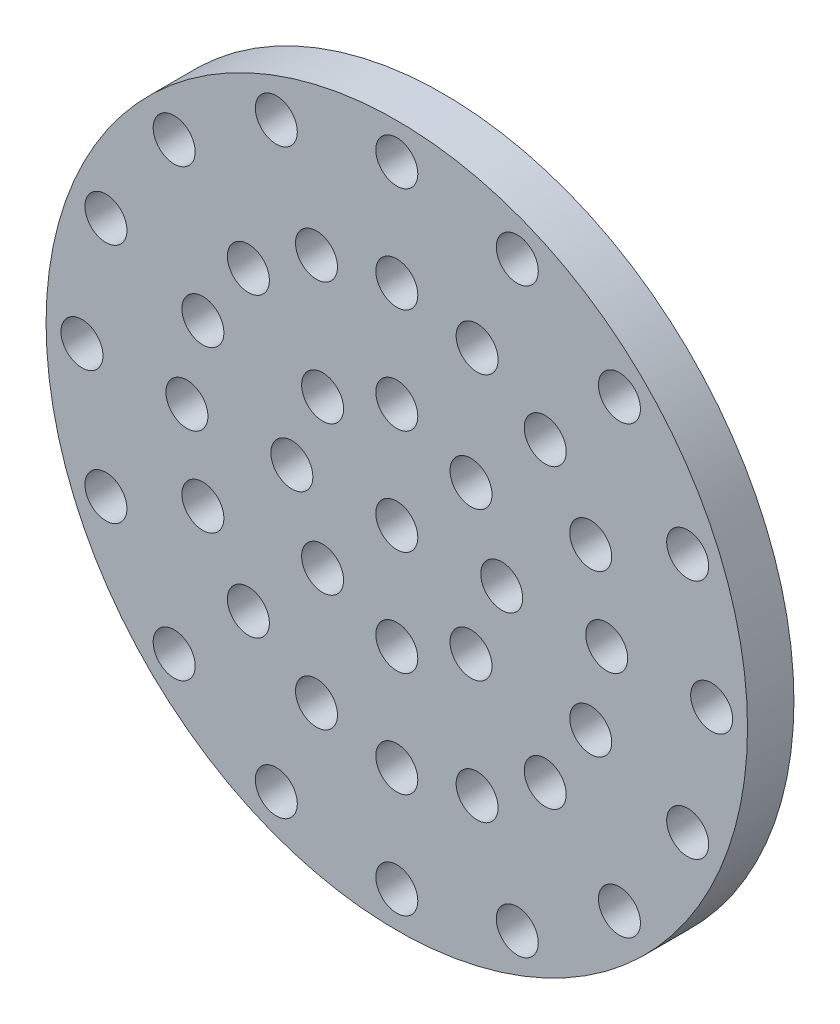
SolidWorks part; units mm, degrees
ref_plane "Front Plane" through (0, 0, 0) normal (0, 0, 1) x (1, 0, 0)
ref_plane "Top Plane" through (0, 0, 0) normal (0, 1, 0) x (1, 0, 0)
ref_plane "Right Plane" through (0, 0, 0) normal (1, 0, 0) x (0, 0, -1)
sketch "Sketch1" plane through (0, 0, 0) normal (0, 0, 1) x (1, 0, 0)
  line L0 (0, 0) -> (5, 0) construction
  circle A0 centre (0, 0) radius 16.71
  circle A1 centre (0, 0) radius 1
  circle A2 centre (5, 0) radius 1
  circle A3 centre (10, 0) radius 1
  circle A4 centre (15, 0) radius 1
  circle A5 centre (3.5355, -3.5355) radius 1
  circle A6 centre (0, -5) radius 1
  circle A7 centre (-3.5355, -3.5355) radius 1
  circle A8 centre (-5, 0) radius 1
  circle A9 centre (-3.5355, 3.5355) radius 1
  circle A10 centre (0, 5) radius 1
  circle A11 centre (3.5355, 3.5355) radius 1
  circle A12 centre (9.2388, -3.8268) radius 1
  circle A13 centre (7.0711, -7.0711) radius 1
  circle A14 centre (3.8268, -9.2388) radius 1
  circle A15 centre (0, -10) radius 1
  circle A16 centre (-3.8268, -9.2388) radius 1
  circle A17 centre (-7.0711, -7.0711) radius 1
  circle A18 centre (-9.2388, -3.8268) radius 1
  circle A19 centre (-10, 0) radius 1
  circle A20 centre (-9.2388, 3.8268) radius 1
  circle A21 centre (-7.0711, 7.0711) radius 1
  circle A22 centre (-3.8268, 9.2388) radius 1
  circle A23 centre (0, 10) radius 1
  circle A24 centre (3.8268, 9.2388) radius 1
  circle A25 centre (7.0711, 7.0711) radius 1
  circle A26 centre (9.2388, 3.8268) radius 1
  circle A27 centre (13.8582, -5.7403) radius 1
  circle A28 centre (10.6066, -10.6066) radius 1
  circle A29 centre (5.7403, -13.8582) radius 1
  circle A30 centre (0, -15) radius 1
  circle A31 centre (-5.7403, -13.8582) radius 1
  circle A32 centre (-10.6066, -10.6066) radius 1
  circle A33 centre (-13.8582, -5.7403) radius 1
  circle A34 centre (-15, 0) radius 1
  circle A35 centre (-13.8582, 5.7403) radius 1
  circle A36 centre (-10.6066, 10.6066) radius 1
  circle A37 centre (-5.7403, 13.8582) radius 1
  circle A38 centre (0, 15) radius 1
  circle A39 centre (5.7403, 13.8582) radius 1
  circle A40 centre (10.6066, 10.6066) radius 1
  circle A41 centre (13.8582, 5.7403) radius 1
  point P28 (0, 0)
  point P59 (0, 0)
  point P91 (0, 0)
  dimension "D1" = 33.42
  dimension "D2" = 5
  dimension "D3" = 4
extrude "Boss-Extrude2" add sketch "Sketch1" along normal blind 2.21
